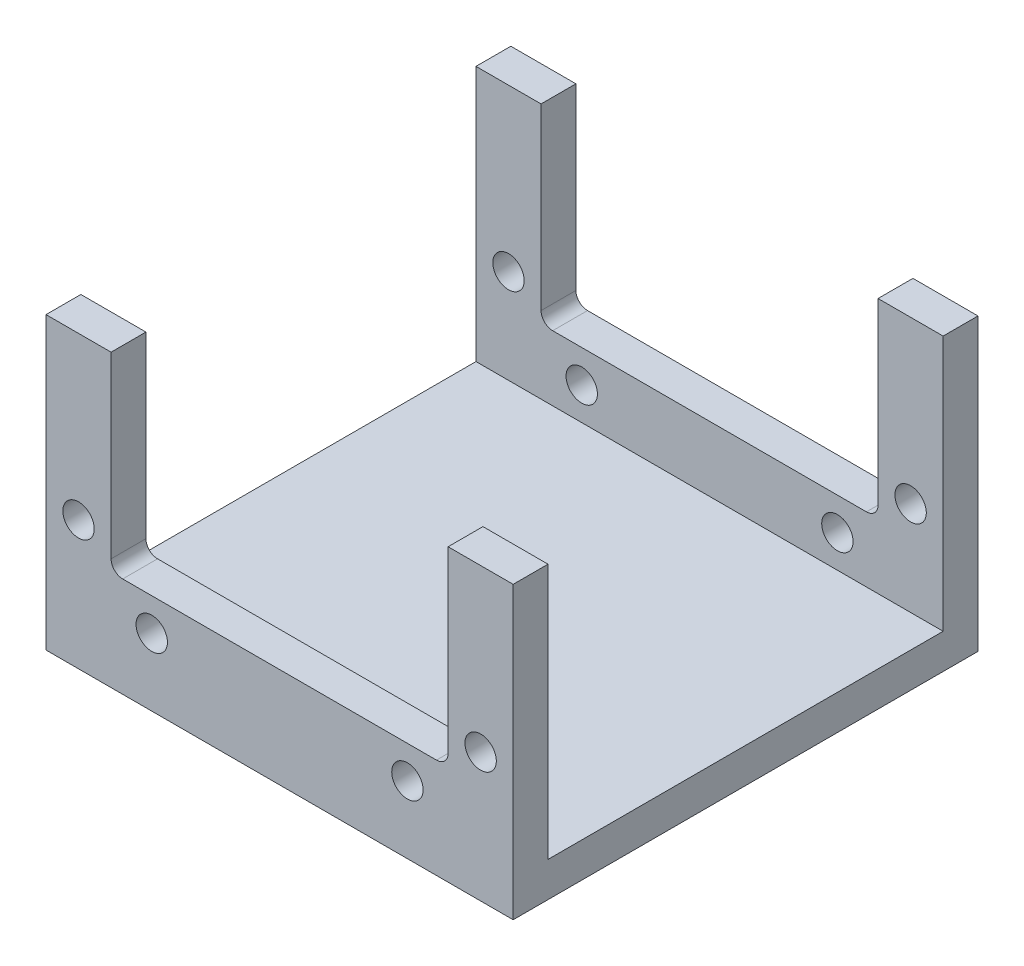
SolidWorks part; units mm, degrees
material "Aluminium 1050"
ref_plane "Front Plane" through (0, 0, 0) normal (0, 0, 1) x (1, 0, 0)
ref_plane "Top Plane" through (0, 0, 0) normal (0, 1, 0) x (1, 0, 0)
ref_plane "Right Plane" through (0, 0, 0) normal (1, 0, 0) x (0, 0, -1)
sketch "Sketch1" plane through (0, 0, 0) normal (1, 0, 0) x (0, 0, -1)
  line L0 (0, 0) -> (40, 0)
  line L1 (40, 0) -> (40, 25)
  line L2 (40, 25) -> (0, 25)
  line L3 (0, 25) -> (0, 0)
  line L4 (3, 25) -> (3, 3)
  line L5 (3, 3) -> (37, 3)
  line L6 (37, 3) -> (37, 25)
  dimension "D1" = 40
  dimension "D2" = 25
  dimension "D3" = 3
extrude "Boss-Extrude1" add sketch "Sketch1" along normal blind 40.2 contours L6 L5 L4 L2 L3 L0 L1
sketch "Sketch2" plane through (0, 0, 0) normal (0, 0, 1) x (1, 0, 0)
  line L0 (20.1, 25) -> (20.1, 8.6)
  line L1 (40.2, 25) -> (0, 25) construction
  line L3 (5.6, 25) -> (5.6, 9.6)
  line L4 (34.6, 25) -> (34.6, 9.6)
  line L5 (5.6, 25) -> (34.6, 25)
  line L6 (6.6, 8.6) -> (33.6, 8.6)
  line L7 (5.6, 41.4) -> (34.6, 41.4)
  line L8 (20.1, 25) -> (20.1, 0) construction
  line L9 (34.6, 25) -> (34.6, 0) construction
  line L10 (5.6, 25) -> (5.6, 0) construction
  line L11 (5.6, 8.6) -> (34.6, 8.6) construction
  arc A0 (34.6, 9.6) -> (33.6, 8.6) centre (33.6, 9.6) cw
  arc A1 (6.6, 8.6) -> (5.6, 9.6) centre (6.6, 9.6) cw
  line M4 (40.2, 25) -> (0, 25)
  dimension "D5" = 1
  dimension "D1" = 14.5
  dimension "D2" = 14.5
  dimension "D3" = 16.4
  dimension "D4" = 16.4
extrude "Cut-Extrude1" cut sketch "Sketch2" against normal through all both and the other way through all contours A1 L6 L0 L3 M4 | A0 L4 L0 L6 M4
sketch "Sketch3" plane through (0, 0, -3) normal (0, 0, -1) x (-1, 0, 0)
  circle A0 centre (-9.1, 5.8) radius 1.35
  circle A1 centre (-2.8, 11.1) radius 1.35
  circle A2 centre (-37.4, 11.1) radius 1.35
  circle A3 centre (-31.1, 5.8) radius 1.35
extrude "Cut-Extrude2" cut sketch "Sketch3" against normal through all both and the other way through all
sketch "Sketch4" plane through (0, 0, 0) normal (-1, 0, 0) x (0, 0, 1)
  line L0 (-20, 0) -> (-20, 27.8578)
  line L1 (0, 0) -> (-40, 0) construction
